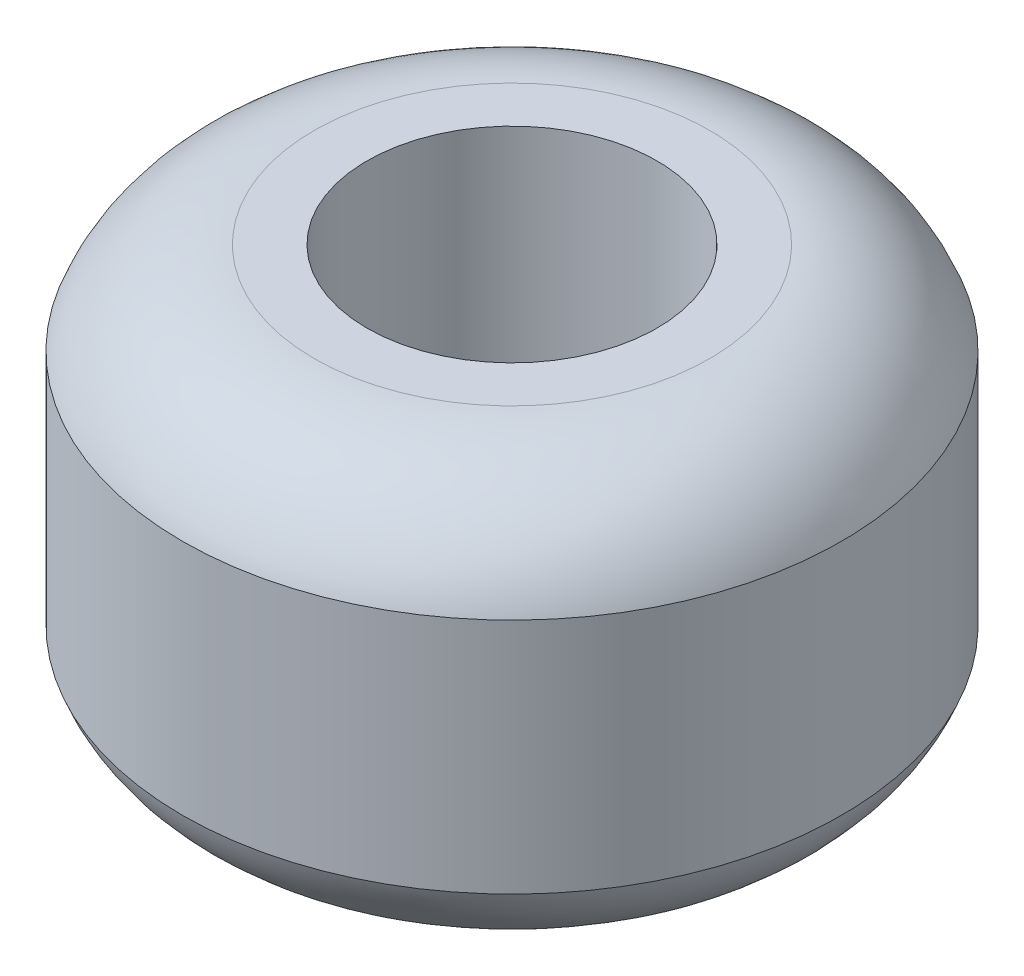
SolidWorks part; units mm, degrees
ref_plane "Front Plane" through (0, 0, 0) normal (0, 0, 1) x (1, 0, 0)
ref_plane "Top Plane" through (0, 0, 0) normal (0, 1, 0) x (1, 0, 0)
ref_plane "Right Plane" through (0, 0, 0) normal (1, 0, 0) x (0, 0, -1)
sketch "Sketch1" plane through (0, 0, 0) normal (0, 0, 1) x (1, 0, 0)
  line L0 (11, 16) -> (11, -16)
  line L1 (11, -16) -> (15, -16)
  line L2 (25, -9) -> (25, 9)
  line L3 (25, 0) -> (11, 0) construction
  line L4 (11, 16) -> (15, 16)
  line L5 (0, 26.1419) -> (0, -22.2587) construction
  arc A0 (15, -16) -> (25, -9) centre (15, -5.3571) ccw
  arc A1 (15, 16) -> (25, 9) centre (15, 5.3571) cw
  dimension "D1" = 25
  dimension "D2" = 11
  dimension "D3" = 16
  dimension "D4" = 4
  dimension "D5" = 7
revolve "Revolve1" add sketch "Sketch1" angle 360 about L5
